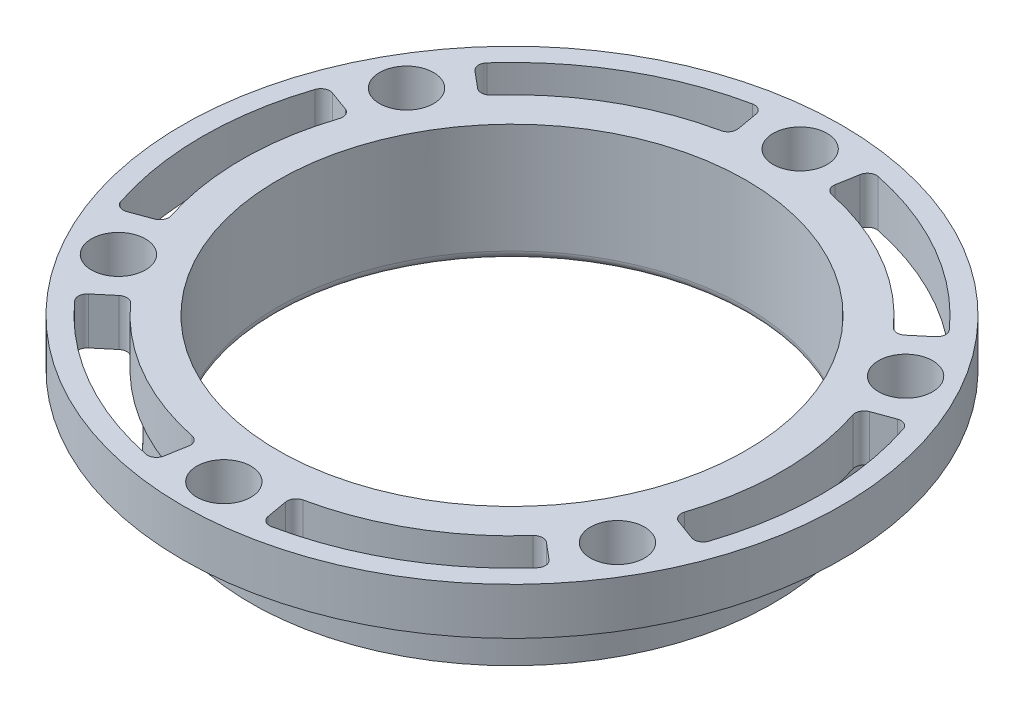
SolidWorks part; units mm, degrees
material "2024-T4"
ref_plane "前视基准面" through (0, 0, 0) normal (0, 0, 1) x (1, 0, 0)
ref_plane "上视基准面" through (0, 0, 0) normal (0, 1, 0) x (1, 0, 0)
ref_plane "右视基准面" through (0, 0, 0) normal (1, 0, 0) x (0, 0, -1)
sketch "草图1" plane through (0, 0, 0) normal (1, 0, 0) x (0, 0, -1)
  line L0 (0, 0) -> (0, 159.2157) construction
  line L1 (-91.5, 33) -> (-91.5, 0)
  line L2 (-91.5, 0) -> (-65, 0)
  line L3 (-65, 0) -> (-65, 3)
  line L6 (-69, 33) -> (-91.5, 33)
  line L7 (-65, 3) -> (-65, 33)
  line L8 (-65, 33) -> (-69, 33)
  dimension "D1" = 130
  dimension "D3" = 33
  dimension "D4" = 3
  dimension "D5" = 183
revolve "旋转1" add sketch "草图1" angle 360 about L0
sketch "草图2" plane through (0, 33, 0) normal (0, 1, 0) x (1, 0, 0)
  circle A0 centre (0, 80) radius 7.5
  dimension "D2" = 15
  dimension "D4" = 80
extrude "切除-拉伸1" cut sketch "草图2" against normal through all
sketch "草图3" plane through (0, 33, 0) normal (0, 1, 0) x (1, 0, 0)
  line L0 (-31.5636, 0) -> (0, 0) construction
  line L1 (0, 0) -> (-70.4769, 25.6515) construction
  line L2 (-72.7883, 26.4928) -> (-78.4292, 28.5459)
  line L3 (-80.8136, 29.4137) -> (-80.8136, -29.4137) construction
  line L4 (-78.4292, -28.5459) -> (-72.7883, -26.4928)
  line L5 (-70.4769, -25.6515) -> (0, 0) construction
  arc A0 (-71.2677, 23.3647) -> (-71.2677, -23.3647) centre (0, 0) ccw
  arc A1 (-81.658, 26.981) -> (-81.658, -26.981) centre (0, 0) ccw
  arc A2 (-81.658, -26.981) -> (-78.4292, -28.5459) centre (-79.2842, -26.1966) ccw
  arc A3 (-71.2677, -23.3647) -> (-72.7883, -26.4928) centre (-73.6433, -24.1435) cw
  arc A4 (-71.2677, 23.3647) -> (-72.7883, 26.4928) centre (-73.6433, 24.1435) ccw
  arc A5 (-81.658, 26.981) -> (-78.4292, 28.5459) centre (-79.2842, 26.1966) cw
  dimension "D2" = 75
  dimension "D3" = 86
  dimension "D4" = 2.5
  dimension "D1" = 40
extrude "切除-拉伸2" cut sketch "草图3" against normal through all
pattern_circular "阵列(圆周)1" count 6 over 360 about axis through (0, 0, 0) along (0, 1, 0) of "切除-拉伸1", "切除-拉伸2"
fillet "圆角1" radius 2.5 2 edges at (0, 0, -65) (0, 0, -91.5)
sketch "草图4" plane through (0, 0, 0) normal (0, -1, 0) x (1, 0, 0)
  circle A0 centre (0, 0) radius 72.5
  circle A1 centre (0, 0) radius 100
  dimension "D1" = 145
  dimension "D2" = 200
extrude "切除-拉伸3" cut sketch "草图4" against normal blind 20
